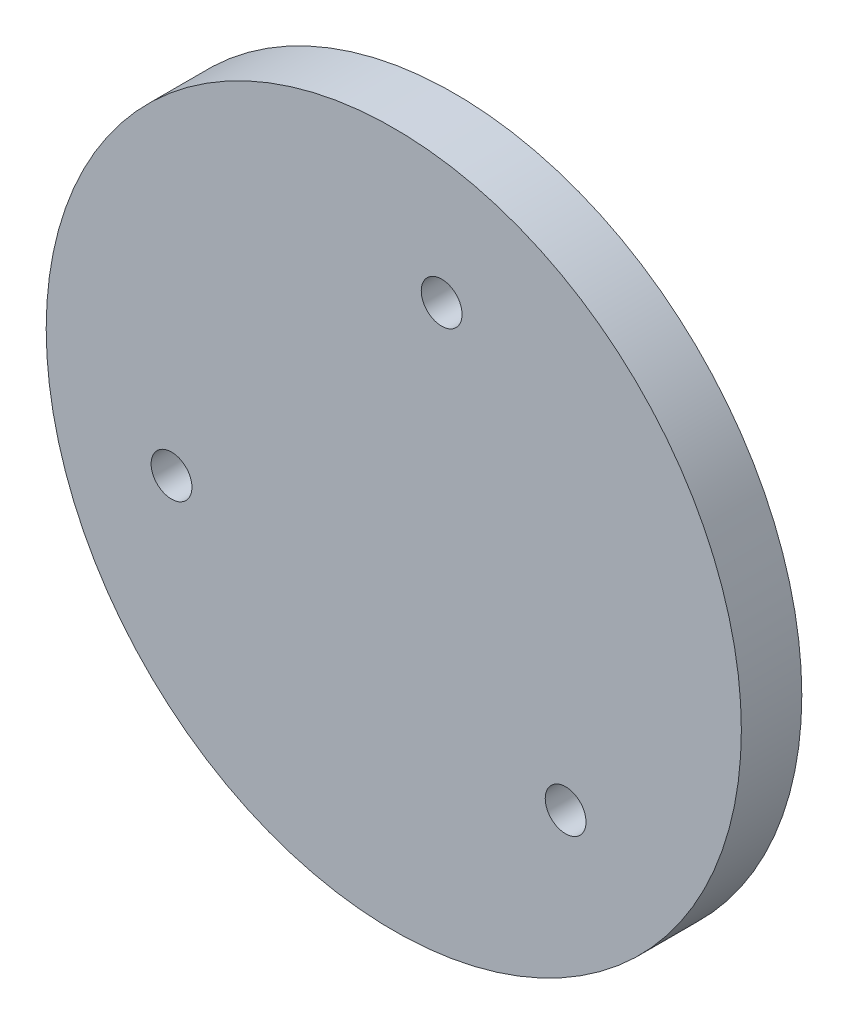
SolidWorks part; units mm, degrees
ref_plane "Plan de face" through (0, 0, 0) normal (0, 0, 1) x (1, 0, 0)
ref_plane "Plan de dessus" through (0, 0, 0) normal (0, 1, 0) x (1, 0, 0)
ref_plane "Plan de droite" through (0, 0, 0) normal (1, 0, 0) x (0, 0, -1)
sketch "Esquisse1" plane through (0, 0, 0) normal (0, 0, 1) x (1, 0, 0)
  circle A0 centre (0, 0) radius 57.5
  dimension "D1" = 115
extrude "Boss.-Extru.1" add sketch "Esquisse1" along normal blind 10
scale "Echelle1" scale about centroid uniform scaling yes scale factor 2
scale "Echelle2" scale about centroid uniform scaling yes scale factor 0.25
sketch "Esquisse2" plane through (0, 0, 2.5) normal (0, 0, -1) x (-1, 0, 0)
  circle A0 centre (-3.9592, 18.2276) radius 1.6875
  circle A1 centre (18.3828, -5.3308) radius 1.6875
  circle A2 centre (-14.2135, -13.007) radius 1.6875
extrude "Enlèv. mat.-Extru.1" cut sketch "Esquisse2" against normal blind 10
